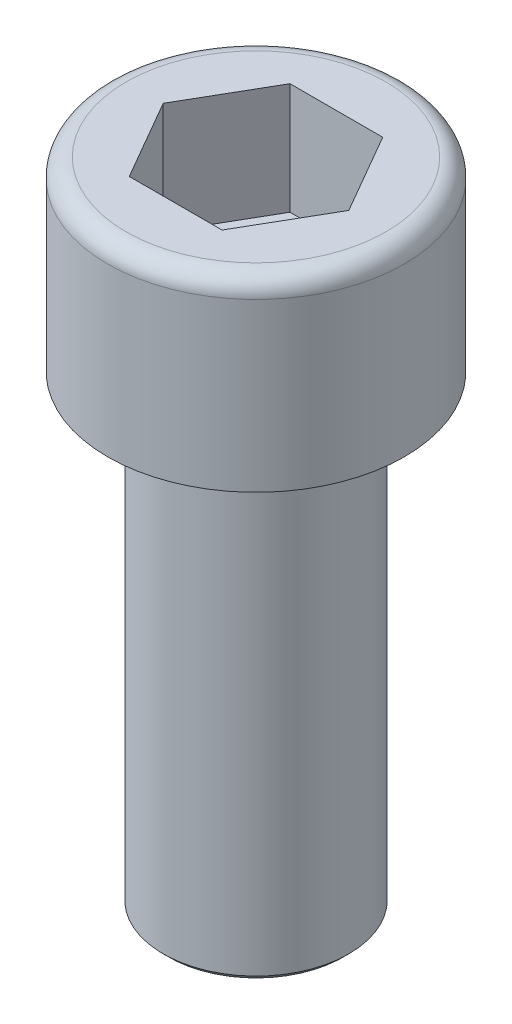
SolidWorks part; units mm, degrees
ref_plane "前视基准面" through (0, 0, 0) normal (0, 0, 1) x (1, 0, 0)
ref_plane "上视基准面" through (0, 0, 0) normal (0, 1, 0) x (1, 0, 0)
ref_plane "右视基准面" through (0, 0, 0) normal (1, 0, 0) x (0, 0, -1)
sketch "草图1" plane through (0, 0, 0) normal (0, 0, 1) x (1, 0, 0)
  line L0 (0, 10) -> (8, 10)
  line L1 (8, 10) -> (8, 0)
  line L2 (8, 0) -> (5, 0)
  line L3 (5, 0) -> (5, -25)
  line L4 (5, -25) -> (0, -25)
  line L5 (0, 10) -> (0, -25)
  line L6 (0, 10) -> (0, 0) construction
  point P9 (5, 10)
  point P10 (8, 4)
  dimension "D1" = 16
  dimension "D2" = 10
  dimension "D3" = 6
  dimension "D" = 10
  dimension "L" = 25
  dimension "D4" = 10
revolve "旋转1" add sketch "草图1" angle 360 about L6
fillet "圆角1" radius 1 1 edges at (-8, 10, 0)
sketch "草图2" plane through (0, 0, 0) normal (0, 1, 0) x (1, 0, 0)
  line L1 (5, 0) -> (2.5, 4.3301)
  line L2 (2.5, 4.3301) -> (-2.5, 4.3301)
  line L3 (-2.5, 4.3301) -> (-5, 0)
  line L4 (-5, 0) -> (-2.5, -4.3301)
  line L5 (-2.5, -4.3301) -> (2.5, -4.3301)
  line L6 (2.5, -4.3301) -> (5, 0)
  circle A0 centre (0, 0) radius 4.3301 construction
extrude "切除-拉伸1" cut sketch "草图2" against normal up to vertex (-4 mm away) from vertex at 10 starting at point (8, 10, 0)
chamfer "倒角1" distance 0.3 angle 45 1 edges at (-5, -25, 0)
equation "\"D2@草图1\" = \"D@草图1\""
equation "\"D3@草图1\" = \"D@草图1\"*0.6"
equation "\"D1@草图1\" = \"D@草图1\"*1.6"
equation "\"D4@草图1\" = \"D@草图1\""
equation "\"D1@圆角1\" = \"D@草图1\"/10"
equation "\"D1@倒角1\" = \"D@草图1\"/100+0.2"
